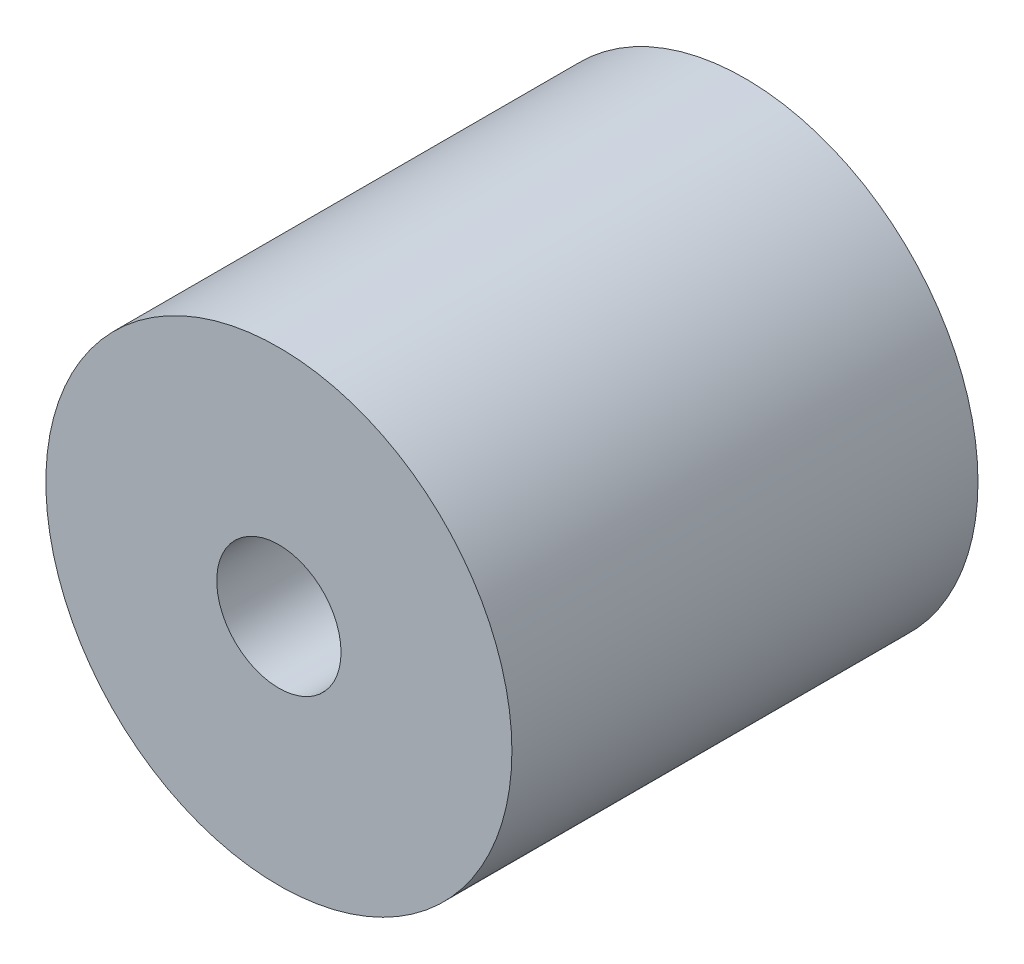
SolidWorks part; units mm, degrees
ref_plane "Front Plane" through (0, 0, 0) normal (0, 0, 1) x (1, 0, 0)
ref_plane "Top Plane" through (0, 0, 0) normal (0, 1, 0) x (1, 0, 0)
ref_plane "Right Plane" through (0, 0, 0) normal (1, 0, 0) x (0, 0, -1)
sketch "Sketch1" plane through (0, 0, 0) normal (0, 0, 1) x (1, 0, 0)
  circle A0 centre (0, 0) radius 15
  dimension "D1" = 30
extrude "Extrude1" add sketch "Sketch1" along normal mid plane 30
sketch "Sketch2" plane through (0, 0, 0) normal (0, 0, 1) x (1, 0, 0)
  circle A0 centre (0, 0) radius 4
  dimension "D1" = 8
extrude "Cut-Extrude1" cut sketch "Sketch2" against normal mid plane 30
